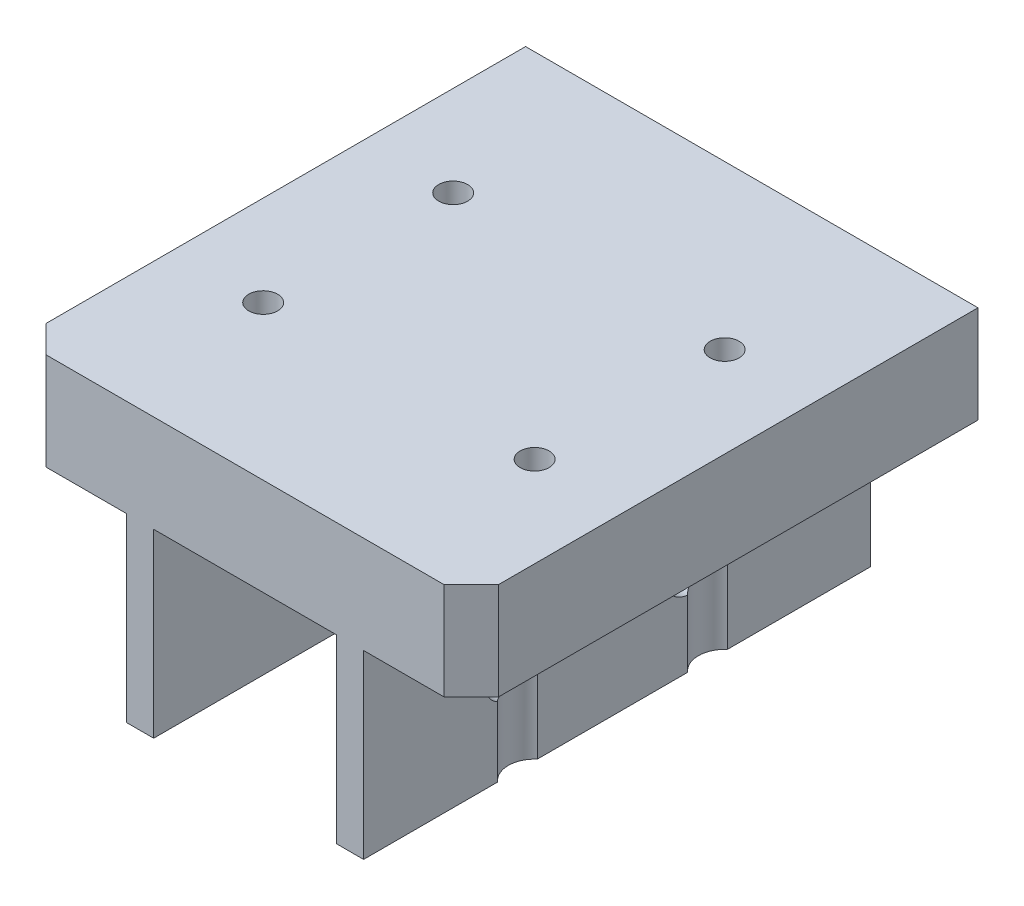
SolidWorks part; units mm, degrees
ref_plane "前视基准面" through (0, 0, 0) normal (0, 0, 1) x (1, 0, 0)
ref_plane "上视基准面" through (0, 0, 0) normal (0, 1, 0) x (1, 0, 0)
ref_plane "右视基准面" through (0, 0, 0) normal (1, 0, 0) x (0, 0, -1)
other "Configuration Table"
sketch "草图1" plane through (0, 0, 0) normal (0, 0, 1) x (1, 0, 0)
  line L2 (-13.1, -14.9614) -> (-10.1, -14.9614)
  line L3 (-25, 5.0386) -> (-25, 15.7886)
  line L4 (-25, 15.7886) -> (25, 15.7886)
  line L5 (25, 5.0386) -> (25, 15.7886)
  line L6 (-13.1, -8.2732) -> (25, 15.7886) construction
  line L7 (-25, 15.7886) -> (13.1, -8.2732) construction
  line L9 (-10.1, -14.9614) -> (-10.1, 5.0386)
  line L11 (-10.1, 5.0386) -> (10.1, 5.0386)
  line L12 (10.1, -14.9614) -> (10.1, 5.0386)
  line L13 (0, -24.3035) -> (10.1, 5.0386) construction
  line L14 (-10.1, 5.0386) -> (0, -24.3035) construction
  line L15 (10.1, -14.9614) -> (13.1, -14.9614)
  line L16 (0, 32.2459) -> (0, -44.1995) construction
  line L19 (25, 5.0386) -> (13.1, 5.0386)
  line L20 (13.1, -14.9614) -> (13.1, 5.0386)
  line L21 (-25, 5.0386) -> (-13.1, 5.0386)
  line L22 (-13.1, -14.9614) -> (-13.1, 5.0386)
  point P0 (0, 0)
  point P7 (0, -24.3035)
  dimension "D1" = 10.75
  dimension "D2" = 20
  dimension "D3" = 3
  dimension "D4" = 20.2
  dimension "D5" = 50
extrude "凸台-拉伸1" add sketch "草图1" along normal blind 53
hole_wizard "孔1" positions "草图4" profile "草图5" legacy end condition through all
sketch "草图4" plane through (0, 5.0386, 0) normal (0, -1, 0) x (-1, 0, 0)
  line L0 (25, -53) -> (25, 0) construction
  line L4 (-15, -15) -> (-15, -36) construction
  line L6 (15, -36) -> (15, -15) construction
  line L8 (-15, -15) -> (-25, -15) construction
  line L9 (-25, -53) -> (-25, 0) construction
  line L12 (-15, -36) -> (-25, -36) construction
  line L14 (15, -36) -> (25, -36) construction
  line L16 (15, -15) -> (25, -15) construction
  line L19 (25, 0) -> (13.1, 0) construction
  line L20 (25, -53) -> (13.1, -53) construction
  point P0 (15, -15)
  point P2 (15, -36)
  point P4 (-15, -15)
  point P6 (-15, -36)
  point P77 (-15, -36)
  dimension "D1" = 10
  dimension "D2" = 15
  dimension "D3" = 17
sketch "草图5" plane through (-15, 5.0386, 15) normal (1, 0, 0) x (0, 0, -1)
  line L0 (0, 0) -> (0, 10.75)
  line L1 (0, 10.75) -> (1.5, 10.75)
  line L2 (1.5, 10.75) -> (1.5, 0)
  line L3 (1.5, 0) -> (0, 0)
  line L4 (0, 110) -> (0, -10) construction
  dimension "直径" = 3
  dimension "深度" = 10.75
sketch "草图6" plane through (0, 5.0386, 0) normal (0, -1, 0) x (1, 0, 0)
  circle A0 centre (15, 36) radius 2.9
  circle A1 centre (15, 15) radius 2.9
  circle A2 centre (-15, 15) radius 2.9
  circle A3 centre (-15, 36) radius 2.9
  dimension "D1" = 5.8
extrude "切除-拉伸1" cut sketch "草图6" along normal through all
chamfer "倒角1" distance 3 angle 45 2 edges at (25, 10.4136, 53) (-25, 10.4136, 53)
hole_wizard "孔2" positions "草图7" profile "草图8" legacy end condition through all
sketch "草图7" plane through (13.1, 0, 0) normal (1, 0, 0) x (0, 0, -1)
  line L0 (-50, 5.0386) -> (0, 5.0386) construction
  line L1 (-53, 5.0386) -> (-38.1909, 5.0386) construction
  line L2 (0, -14.9614) -> (0, 5.0386) construction
  line L3 (-53, -14.9614) -> (-53, 5.0386) construction
  point P0 (-17, -4.9614)
  point P2 (-37, -4.9614)
  dimension "D1" = 10
  dimension "D2" = 10
  dimension "D3" = 17
  dimension "D4" = 16
sketch "草图8" plane through (13.1, -4.9614, 17) normal (0, 1, 0) x (0, 0, -1)
  line L0 (0, 0) -> (0, 38.1)
  line L1 (0, 38.1) -> (2.6, 38.1)
  line L2 (2.6, 38.1) -> (2.6, 0)
  line L3 (2.6, 0) -> (0, 0)
  line L4 (0, 110) -> (0, -10) construction
  dimension "直径" = 5.2
  dimension "深度" = 38.1
hole_wizard "M3 十字槽沉头木螺钉的锥形沉头孔1" positions "草图9" profile "草图10" countersink size "M3" standard "GB"
sketch "草图9" plane through (0, 5.0386, 0) normal (0, -1, 0) x (-1, 0, 0)
  point P0 (-15, -15)
  point P3 (15, -15)
  point P6 (15, -36)
  point P9 (-15, -36)
sketch "草图10" plane through (15, 5.0386, 15) normal (1, 0, 0) x (0, 0, -1)
  line L0 (0, 0) -> (0, 10.75)
  line L1 (0, 10.75) -> (1.6, 10.75)
  line L2 (1.6, 10.75) -> (1.6, 1.7)
  line L3 (1.6, 1.7) -> (3.3, 0)
  line L5 (3.3, 0) -> (0, 0)
  line L6 (-1.6, 1.7) -> (-3.3, 0) construction
  line L11 (0, -6.35) -> (0, 107.95) construction
  dimension "通孔孔直径" = 3.2
  dimension "通孔孔深度" = 10.75
  dimension "近端锥形沉头孔直径" = 6.6
  dimension "近端锥形沉头孔角度" = 90
sketch "草图11" plane through (0, 5.0386, 0) normal (0, -1, 0) x (1, 0, 0)
  circle A0 centre (15, 36) radius 3.3
  circle A1 centre (15, 15) radius 3.3
  circle A2 centre (-15, 15) radius 3.3
  circle A3 centre (-15, 36) radius 3.3
extrude "切除-拉伸2" [suppressed] cut sketch "草图11" along normal through all draft 9
sketch "草图12" plane through (0, 0, 0) normal (0, 0, -1) x (-1, 0, 0)
  line L0 (-10.1, 5.0386) -> (10.1, 5.0386)
  line L1 (-25, 15.7886) -> (25, 15.7886)
  line L2 (-25, 15.7886) -> (-25, 5.0386)
  line L3 (-25, 5.0386) -> (-13.1, 5.0386)
  line L4 (25, 15.7886) -> (25, 5.0386)
  line L6 (-13.1, 5.0386) -> (-13.1, -14.9614)
  line L7 (-13.1, -14.9614) -> (-10.1, -14.9614)
  line L8 (-10.1, 5.0386) -> (-10.1, -14.9614)
  line L9 (13.1, -14.9614) -> (10.1, -14.9614)
  line L10 (13.1, -14.9614) -> (13.1, 5.0386)
  line L12 (10.1, -14.9614) -> (10.1, 5.0386)
  line L13 (13.1, 5.0386) -> (25, 5.0386)
extrude "凸台-拉伸2" add sketch "草图12" along normal blind 3
